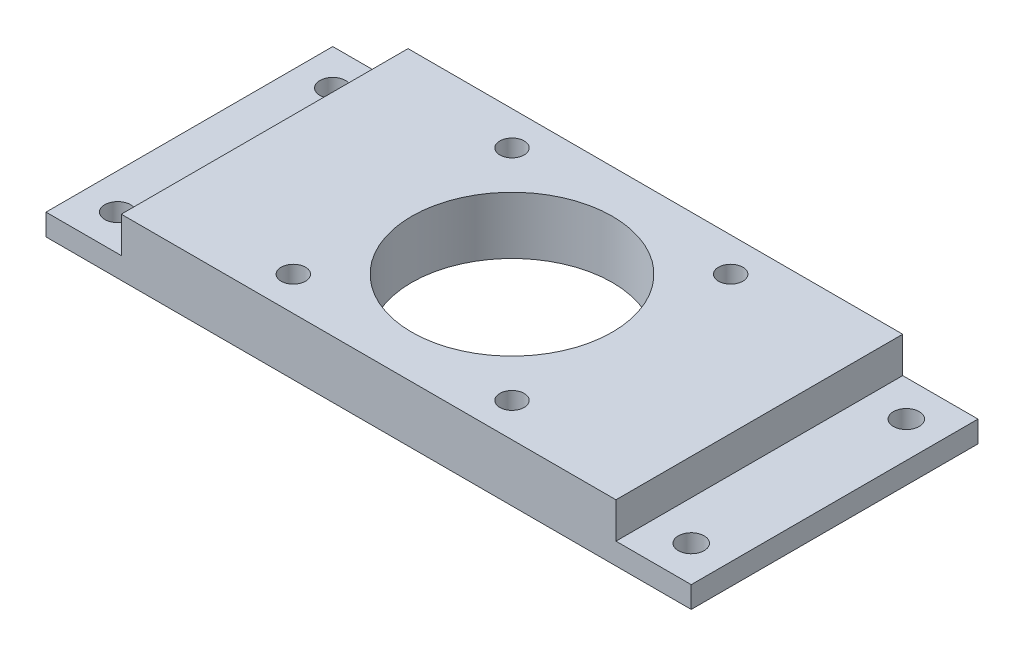
SolidWorks part; units mm, degrees
ref_plane "Front Plane" through (0, 0, 0) normal (0, 0, 1) x (1, 0, 0)
ref_plane "Top Plane" through (0, 0, 0) normal (0, 1, 0) x (1, 0, 0)
ref_plane "Right Plane" through (0, 0, 0) normal (1, 0, 0) x (0, 0, -1)
sketch "Sketch1" plane through (0, 0, 0) normal (0, 1, 0) x (1, 0, 0)
  line L1 (-35, -20) -> (35, -20)
  line L2 (-35, -20) -> (-35, 20)
  line L3 (-35, 20) -> (35, 20)
  line L4 (35, -20) -> (35, 20)
  line L5 (-35, -20) -> (35, 20) construction
  line L6 (-35, 20) -> (35, -20) construction
  point P0 (0, 0)
  dimension "D1" = 70
  dimension "D2" = 40
extrude "Boss-Extrude1" add sketch "Sketch1" along normal blind 5
sketch "Sketch2" plane through (0, 0, 0) normal (0, -1, 0) x (1, 0, 0)
  line L0 (-35, 20) -> (35, 20) construction
  line L1 (-45, -20) -> (45, -20)
  line L2 (-45, -20) -> (-45, 20)
  line L3 (-45, 20) -> (45, 20)
  line L4 (45, -20) -> (45, 20)
  line L5 (-45, -20) -> (45, 20) construction
  line L6 (-45, 20) -> (45, -20) construction
  line L7 (-35, -20) -> (-35, 20) construction
  point P0 (0, 0)
  dimension "D1" = 10
extrude "Boss-Extrude2" add sketch "Sketch2" along normal blind 3
sketch "Sketch3" plane through (0, 0, 0) normal (0, 1, 0) x (1, 0, 0)
  line L0 (-45, -20) -> (-45, 20) construction
  line L1 (-40, -15) -> (40, -15)
  line L2 (-40, -15) -> (-40, 15)
  line L3 (-40, 15) -> (40, 15)
  line L4 (40, -15) -> (40, 15)
  line L5 (-40, -15) -> (40, 15) construction
  line L6 (-40, 15) -> (40, -15) construction
  line L7 (-45, 20) -> (-35, 20) construction
  point P0 (0, 0)
  dimension "D1" = 5
  dimension "D2" = 5
hole_wizard "M3 Clearance Hole1" positions "Sketch4" profile "Sketch5" hole size "M3" standard "ANSI Metric" end condition through all
sketch "Sketch4" plane through (0, 0, 0) normal (0, 1, 0) x (1, 0, 0)
  point P0 (-40, 15)
  point P3 (-40, -15)
  point P6 (40, 15)
  point P9 (40, -15)
sketch "Sketch5" plane through (-40, 0, -15) normal (1, 0, 0) x (0, 0, 1)
  line L0 (0, 0) -> (0, 3)
  line L1 (0, 3) -> (1.8, 3)
  line L2 (1.8, 3) -> (1.8, 0)
  line L5 (1.8, 0) -> (0, 0)
  line L11 (0, -6.35) -> (0, 107.95) construction
  dimension "Thru Hole Dia." = 3.6
  dimension "Thru Hole Depth" = 3
hole_wizard "M3 Clearance Hole2" positions "Sketch6" profile "Sketch7" hole size "M3" standard "ANSI Metric" end condition through all
sketch "Sketch6" plane through (0, 5, 0) normal (0, 1, 0) x (1, 0, 0)
  line L1 (-15.25, -15.25) -> (15.25, -15.25)
  line L2 (-15.25, -15.25) -> (-15.25, 15.25)
  line L3 (-15.25, 15.25) -> (15.25, 15.25)
  line L4 (15.25, -15.25) -> (15.25, 15.25)
  line L5 (-15.25, -15.25) -> (15.25, 15.25) construction
  line L6 (-15.25, 15.25) -> (15.25, -15.25) construction
  point P1 (0, 0)
  point P2 (15.25, 15.25)
  point P61 (-15.25, -15.25)
  point P62 (-15.25, 15.25)
  point P63 (15.25, -15.25)
  dimension "D1" = 30.5
  dimension "D2" = 30.5
sketch "Sketch7" plane through (0, 5, 0) normal (1, 0, 0) x (0, 0, 1)
  line L0 (0, 0) -> (0, 8)
  line L1 (0, 8) -> (1.7, 8)
  line L2 (1.7, 8) -> (1.7, 0)
  line L5 (1.7, 0) -> (0, 0)
  line L11 (0, -6.35) -> (0, 107.95) construction
  dimension "Thru Hole Dia." = 3.4
  dimension "Thru Hole Depth" = 8
sketch "Sketch9" plane through (0, 5, 0) normal (0, 1, 0) x (1, 0, 0)
  circle A0 centre (0, 0) radius 14
  dimension "D1" = 28
extrude "Cut-Extrude1" cut sketch "Sketch9" against normal through all
sketch "Sketch10" plane through (-35, 0, 0) normal (-1, 0, 0) x (0, 0, 1)
  line L4 (-20, 0) -> (20, 0)
  line L5 (20, 0) -> (20, 5)
  line L6 (20, 5) -> (-20, 5)
  line L7 (-20, 5) -> (-20, 0)
  line L8 (-20, 0) -> (20, 0)
  line L9 (20, 0) -> (20, 5)
  line L10 (20, 5) -> (-20, 5)
  line L11 (-20, 5) -> (-20, 0)
  dimension "D1" = 0
extrude "Cut-Extrude2" cut sketch "Sketch10" against normal blind 0.5
mirror "Mirror1" about plane through (0, 0, 0) normal (1, 0, 0) of "Cut-Extrude2"
equation "\"8`\"=84.8464"
